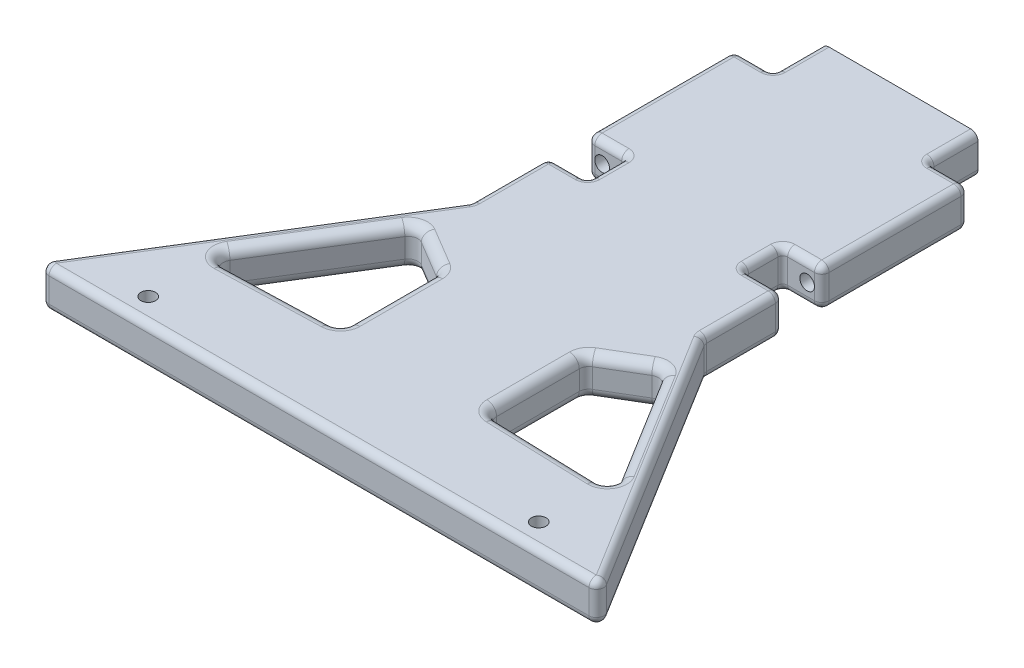
SolidWorks part; units mm, degrees
ref_plane "Front Plane" through (0, 0, 0) normal (0, 0, 1) x (1, 0, 0)
ref_plane "Top Plane" through (0, 0, 0) normal (0, 1, 0) x (1, 0, 0)
ref_plane "Right Plane" through (0, 0, 0) normal (1, 0, 0) x (0, 0, -1)
sketch "Sketch1" plane through (0, 0, 0) normal (0, 1, 0) x (1, 0, 0)
  line L0 (0, 0) -> (116, 0)
  line L1 (116, 0) -> (82, 55)
  line L2 (82, 55) -> (34, 55) construction
  line L3 (34, 55) -> (0, 0)
  line L4 (74, 119) -> (74, 109)
  line L5 (82, 55) -> (34, 55) construction
  line L6 (82, 55) -> (82, 71)
  line L7 (74, 119) -> (42, 119)
  line L8 (34, 55) -> (34, 71)
  line L9 (74, 71) -> (82, 71)
  line L10 (34, 71) -> (42, 71)
  line L11 (42, 71) -> (42, 79)
  line L12 (74, 109) -> (82, 109)
  line L13 (42, 109) -> (34, 109)
  line L14 (42, 79) -> (34, 79)
  line L15 (74, 79) -> (82, 79)
  line L16 (42, 109) -> (42, 119)
  line L17 (74, 79) -> (74, 71)
  line L18 (82, 79) -> (82, 109)
  line L19 (34, 79) -> (34, 109)
  line L20 (58, 0) -> (58, 135.9717) construction
  line L21 (43, 19.4505) -> (73, 19.4505) construction
  line L22 (73, 19.4505) -> (73, 39.4505)
  line L23 (73, 39.4505) -> (83.3079, 45.5943)
  line L24 (83.3079, 45.5943) -> (99.987, 18.6134)
  line L25 (99.987, 18.6134) -> (73, 19.4505)
  line L26 (58, 119) -> (58, 0)
  point P5 (58, 55)
  point P6 (58, 0)
  point P26 (58, 19.4505)
  dimension "D1" = 116
  dimension "D2" = 48
  dimension "D3" = 55
  dimension "D4" = 30
  dimension "D5" = 8
  dimension "D6" = 8
  dimension "D7" = 30
  dimension "D8" = 10
  dimension "D9" = 8
  dimension "D10" = 20
  dimension "D11" = 27
  dimension "D12" = 12
extrude "Boss-Extrude1" add sketch "Sketch1" along normal blind 8 contours L7 L26 L0 L1 L6 L9 L17 L15 L18 L12 L4 L24 L25 L22 L23
fillet "Fillet1" radius 1 3 edges at (74, 4, -71) (74, 4, -79) (74, 4, -109)
fillet "Fillet2" radius 1.5 29 edges at (82, 8, -63) (74, 8, -114.5) (74.2929, 8, -109.2929) (78.5, 8, -79) (74.2929, 8, -78.7071) (74, 8, -75) (74.2929, 8, -71.2929) (78.5, 0, -109) (74.2929, 0, -109.2929) (78.5, 0, -79) (74.2929, 0, -78.7071) (78.5, 0, -71) (74.2929, 0, -71.2929) (116, 4, 0) (78.5, 8, -109) (82, 8, -94) (78.5, 8, -71) (82, 4, -55) (99, 8, -27.5) (87, 8, 0) (74, 0, -114.5) (74, 0, -75) (82, 0, -94) (82, 0, -63) (99, 0, -27.5) (87, 0, 0) (82, 4, -109) (82, 4, -71) (82, 4, -79)
fillet "Fillet3" radius 2 12 edges at (86.4935, 8, -19.0319) (86.4935, 0, -19.0319) (78.154, 8, -42.5224) (78.154, 0, -42.5224) (83.3079, 4, -45.5943) (91.6475, 8, -32.1038) (99.987, 4, -18.6134) (91.6475, 0, -32.1038) (73, 4, -19.4505) (73, 8, -29.4505) (73, 4, -39.4505) (73, 0, -29.4505)
sketch "Sketch2" plane through (0, 0, -109) normal (0, 0, -1) x (-1, 0, 0)
  line L0 (-82, 4) -> (-68.7869, 4) construction
  line L1 (-82, 6.5) -> (-82, 1.5) construction
  circle A0 centre (-79, 4) radius 1.5
  dimension "D1" = 3
  dimension "D2" = 3
extrude "Cut-Extrude1" cut sketch "Sketch2" against normal blind 47
sketch "Sketch3" plane through (0, 8, 0) normal (0, 1, 0) x (1, 0, 0)
  line L0 (113.3093, 0) -> (58, 0) construction
  line L1 (58, 119) -> (58, 1.5) construction
  circle A0 centre (98, 5) radius 1.5
  dimension "D1" = 3
  dimension "D2" = 5
  dimension "D3" = 40
extrude "Cut-Extrude2" cut sketch "Sketch3" against normal through all
mirror "Mirror1" about plane through (58, 8, 0) normal (1, 0, 0) of bodies 104 101
